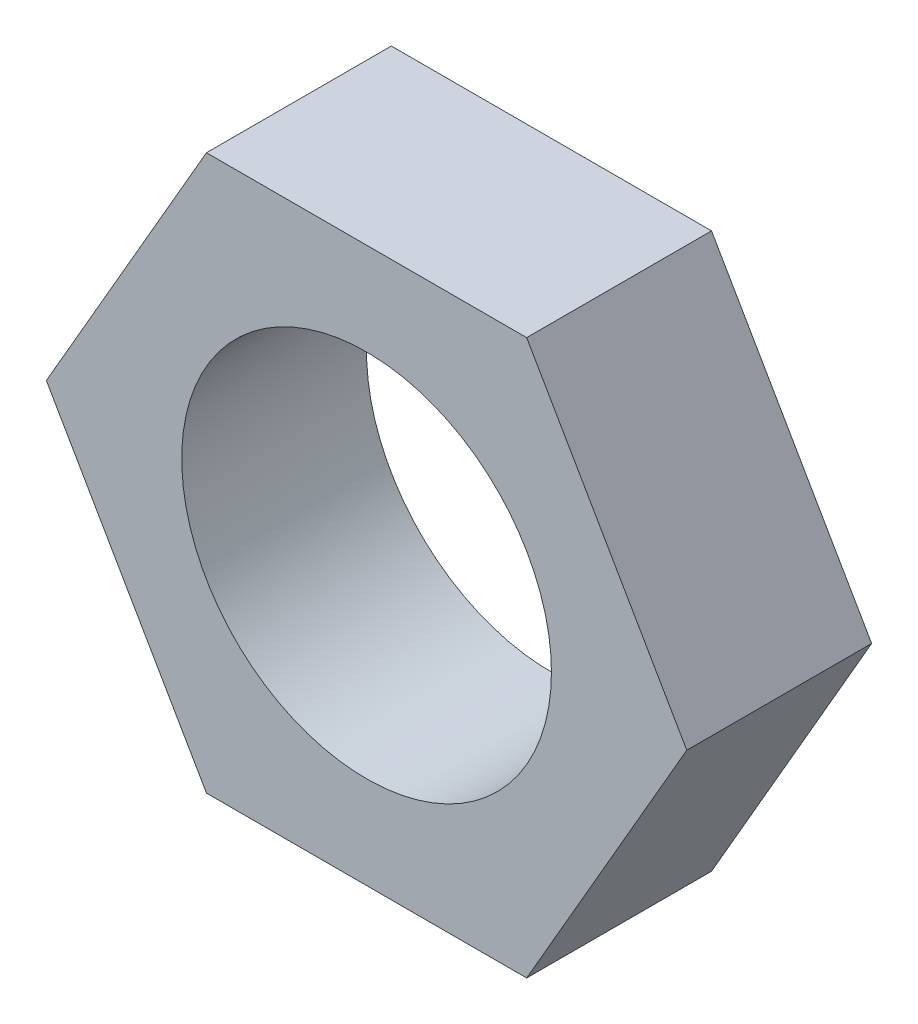
SolidWorks part; units mm, degrees
ref_plane "前视基准面" through (0, 0, 0) normal (0, 0, 1) x (1, 0, 0)
ref_plane "上视基准面" through (0, 0, 0) normal (0, 1, 0) x (1, 0, 0)
ref_plane "右视基准面" through (0, 0, 0) normal (1, 0, 0) x (0, 0, -1)
sketch "草图1" plane through (0, 0, 0) normal (0, 0, 1) x (1, 0, 0)
  line L1 (4.3301, -7.5) -> (8.6603, 0)
  line L2 (8.6603, 0) -> (4.3301, 7.5)
  line L3 (4.3301, 7.5) -> (-4.3301, 7.5)
  line L4 (-4.3301, 7.5) -> (-8.6603, 0)
  line L5 (-8.6603, 0) -> (-4.3301, -7.5)
  line L6 (-4.3301, -7.5) -> (4.3301, -7.5)
  circle A0 centre (0, 0) radius 7.5 construction
  dimension "D1" = 15
extrude "凸台-拉伸1" add sketch "草图1" along normal blind 5
sketch "草图2" plane through (0, 0, 5) normal (0, 0, 1) x (1, 0, 0)
  circle A0 centre (0, 0) radius 5
  dimension "D1" = 10
extrude "切除-拉伸1" cut sketch "草图2" against normal through all
